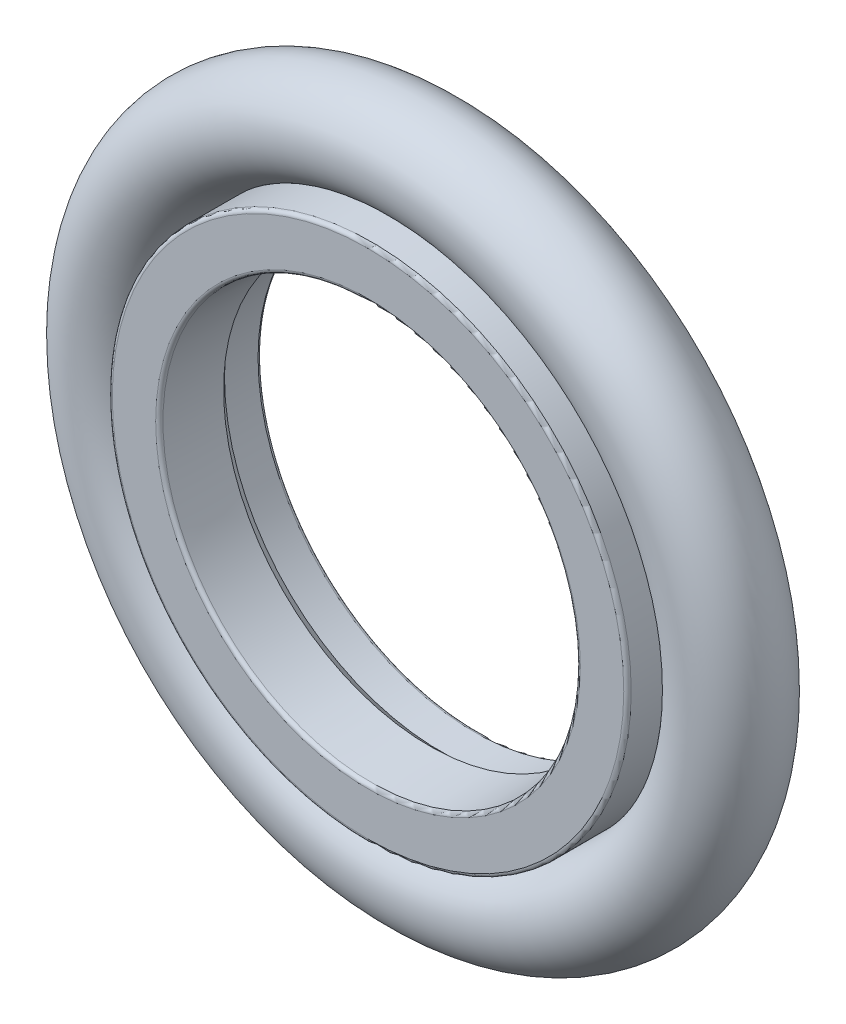
SolidWorks part; units mm, degrees
ref_plane "Front Plane" through (0, 0, 0) normal (0, 0, 1) x (1, 0, 0)
ref_plane "Top Plane" through (0, 0, 0) normal (0, 1, 0) x (1, 0, 0)
ref_plane "Right Plane" through (0, 0, 0) normal (1, 0, 0) x (0, 0, -1)
sketch "Sketch1" plane through (0, 0, 0) normal (1, 0, 0) x (0, 0, -1)
  line L0 (0, 0) -> (69.0954, 0) construction
  line L1 (0.1, 6.96) -> (2.85, 6.96)
  line L2 (0, 6.86) -> (0, 5.6956)
  line L3 (2.95, 6.86) -> (2.95, 5.9)
  line L4 (2.85, 5.8) -> (1.95, 5.8)
  line L5 (1.95, 5.8) -> (1.65, 5.525)
  line L6 (1.65, 5.525) -> (0.0955, 5.5957)
  arc A0 (0, 5.6956) -> (0.0955, 5.5957) centre (0.1, 5.6956) ccw
  arc A1 (2.95, 5.9) -> (2.85, 5.8) centre (2.85, 5.9) cw
  arc A2 (0.1, 6.96) -> (0, 6.86) centre (0.1, 6.86) ccw
  arc A3 (2.95, 6.86) -> (2.85, 6.96) centre (2.85, 6.86) ccw
  point P11 (0, 5.6)
  dimension "D8" = 0.1
  dimension "D1" = 1
  dimension "D2" = 1.3
  dimension "D3" = 2.95
  dimension "D4" = 11.2
  dimension "D5" = 13.92
  dimension "D6" = 11.05
  dimension "D7" = 11.6
revolve "Revolve1" add sketch "Sketch1" angle 360 about L0
sketch "Sketch2" plane through (0, 0, 0) normal (1, 0, 0) x (0, 0, -1)
  line L0 (1.475, 6.96) -> (1.475, 10.528) construction
  line L1 (2.85, 6.96) -> (0.1, 6.96) construction
  line L2 (0, 0) -> (10.3771, 0) construction
  circle A0 centre (1.475, 8.26) radius 1.3
  dimension "D1" = 2.6
  dimension "D2" = 19.12
revolve "Revolve2" add sketch "Sketch2" angle 360 about L2
